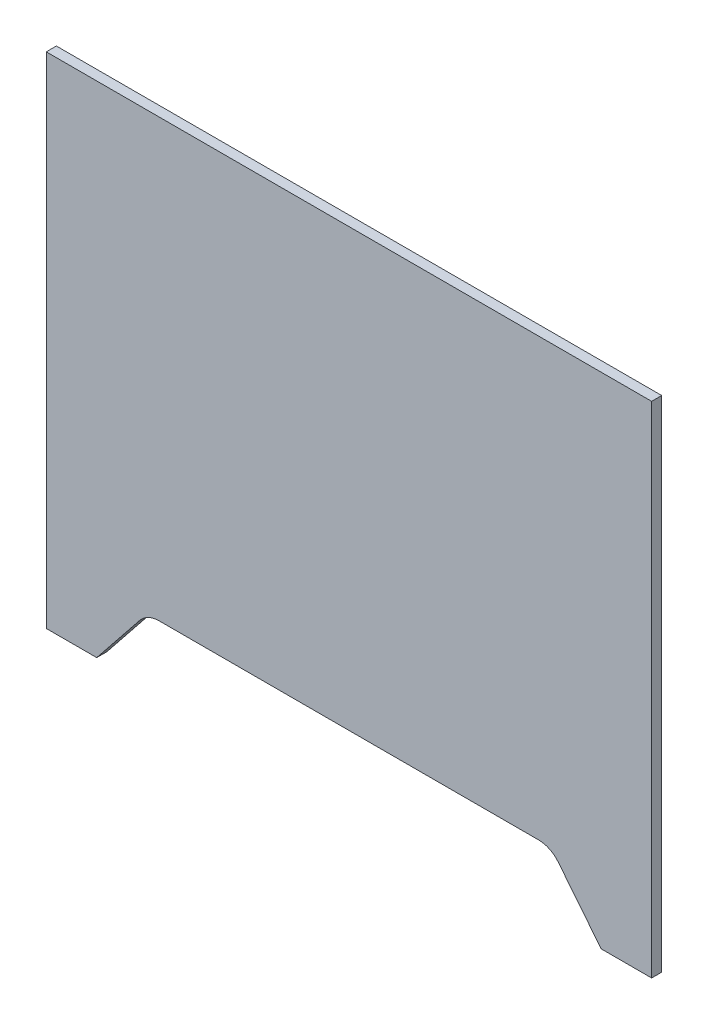
SolidWorks part; units mm, degrees
ref_plane "前视基准面" through (0, 0, 0) normal (0, 0, 1) x (1, 0, 0)
ref_plane "上视基准面" through (0, 0, 0) normal (0, 1, 0) x (1, 0, 0)
ref_plane "右视基准面" through (0, 0, 0) normal (1, 0, 0) x (0, 0, -1)
sketch "Sketch1" plane through (0, 0, 0) normal (0, 0, 1) x (1, 0, 0)
  line L0 (0, -99) -> (0, 0) construction
  line L1 (-120, -99) -> (120, -99) construction
  line L2 (-120, -99) -> (-120, 99)
  line L3 (-120, 99) -> (120, 99)
  line L4 (120, -99) -> (120, 99)
  line L5 (-120, -99) -> (120, 99) construction
  line L6 (-120, 99) -> (120, -99) construction
  line L7 (-75.1938, -74) -> (75.1938, -74)
  line L8 (83.0024, -77.753) -> (100, -99)
  line L9 (100, -99) -> (120, -99)
  line L10 (-100, -99) -> (-120, -99)
  line L11 (-83.0024, -77.753) -> (-100, -99)
  arc A0 (83.0024, -77.753) -> (75.1938, -74) centre (75.1938, -84) ccw
  arc A1 (-83.0024, -77.753) -> (-75.1938, -74) centre (-75.1938, -84) cw
  point P0 (0, 0)
  point P13 (80, -74)
  point P18 (0, -74)
  dimension "D6" = 10
  dimension "D1" = 240
  dimension "D2" = 198
  dimension "D3" = 25
  dimension "D4" = 20
  dimension "D5" = 80
extrude "Boss-Extrude1" add sketch "Sketch1" along normal blind 4
